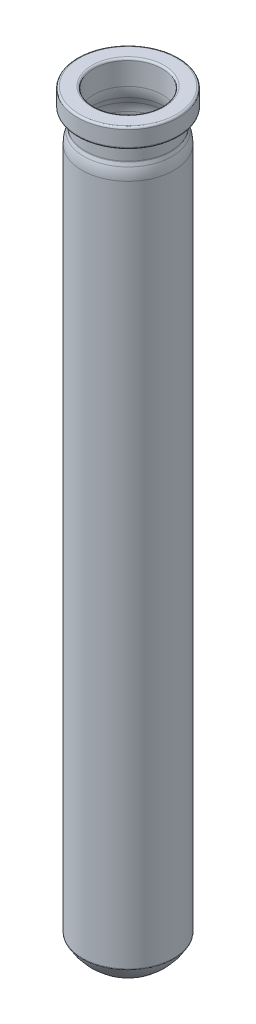
SolidWorks part; units mm, degrees
material "Glass"
ref_plane "Front Plane" through (0, 0, 0) normal (0, 0, 1) x (1, 0, 0)
ref_plane "Top Plane" through (0, 0, 0) normal (0, 1, 0) x (1, 0, 0)
ref_plane "Right Plane" through (0, 0, 0) normal (1, 0, 0) x (0, 0, -1)
sketch "Sketch1" plane through (0, 0, 0) normal (0, 0, 1) x (1, 0, 0)
  line L0 (0, -45.5603) -> (0, 188.3768) construction
  line L1 (0, 0) -> (194.5038, 0) construction
  line L2 (-9.017, 5.6538) -> (-9.017, 139.4932)
  line L3 (-9.5377, 149.3012) -> (-7.0866, 149.3012)
  line L4 (0, 149.3012) -> (194.5038, 149.3012) construction
  line L5 (-9.9187, 148.9202) -> (-9.9187, 145.8976)
  line L6 (-9.5377, 145.5166) -> (-8.7503, 145.5166)
  line L7 (-8.3693, 145.1356) -> (-8.3693, 142.4596)
  line L8 (-25.9817, 188.3768) -> (20.0145, 188.3768) construction
  line L9 (-8.3923, 142.3293) -> (-8.634, 141.665)
  line L10 (-6.7056, 148.9202) -> (-6.7056, 144.5184)
  line L11 (-7.7978, 8.4125) -> (-7.7978, 139.4932)
  line L12 (-7.0886, 142.3465) -> (-7.4884, 141.248)
  line L13 (-7.2236, 141.9754) -> (-7.4884, 141.248) construction
  line L14 (-9.017, 5.5626) -> (-9.017, 139.4932) construction
  line L15 (-7.7978, 5.5626) -> (-7.7978, 139.4932) construction
  line L16 (0, 1.524) -> (0, 0)
  line L17 (-8.3693, 142.3924) -> (-8.634, 141.665) construction
  arc A0 (-8.9749, 5.4797) -> (0, 0) centre (0, 10.0896) ccw
  arc A1 (-9.017, 139.4932) -> (-8.634, 141.665) centre (-2.667, 139.4932) cw
  arc A2 (-7.7978, 139.4932) -> (-7.4884, 141.248) centre (-2.667, 139.4932) cw
  arc A3 (-7.0886, 142.3465) -> (-6.7056, 144.5184) centre (-13.0556, 144.5184) ccw
  arc A4 (-5.5973, 3.6058) -> (0, 1.524) centre (0, 10.0896) ccw
  arc A5 (-7.655, 6.2464) -> (0, 1.524) centre (0, 10.0896) ccw construction
  arc A6 (-5.5973, 3.6058) -> (-7.7978, 8.4125) centre (-1.4478, 8.4125) cw
  arc A7 (-9.017, 5.5626) -> (0, 0) centre (0, 10.0896) ccw construction
  arc A8 (-8.9749, 5.4797) -> (-9.017, 5.6538) centre (-8.636, 5.6538) cw
  arc A9 (-8.3693, 142.4596) -> (-8.3923, 142.3293) centre (-8.7503, 142.4596) cw
  arc A10 (-8.7503, 145.5166) -> (-8.3693, 145.1356) centre (-8.7503, 145.1356) cw
  arc A11 (-9.9187, 145.8976) -> (-9.5377, 145.5166) centre (-9.5377, 145.8976) ccw
  arc A12 (-9.9187, 148.9202) -> (-9.5377, 149.3012) centre (-9.5377, 148.9202) cw
  arc A13 (-6.7056, 148.9202) -> (-7.0866, 149.3012) centre (-7.0866, 148.9202) ccw
  point P36 (-9.017, 5.5626)
  point P40 (-8.3693, 142.3924)
  point P43 (-8.3693, 145.5166)
  point P46 (-9.9187, 145.5166)
  point P49 (-9.9187, 149.3012)
  dimension "D1" = 18.034
  dimension "D9" = 6.35
  dimension "D11" = 6.35
  dimension "D13" = 6.35
  dimension "D14" = 1.524
  dimension "D15" = 0.381
  dimension "D2" = 5.5626
  dimension "D3" = 149.3012
  dimension "D4" = 19.8374
  dimension "D5" = 16.7386
  dimension "D6" = 3.7846
  dimension "D7" = 3.1242
  dimension "D8" = 20
  dimension "D10" = 13.4112
  dimension "D12" = 1.2192
revolve "Revolve1" add sketch "Sketch1" angle 360 about L0
